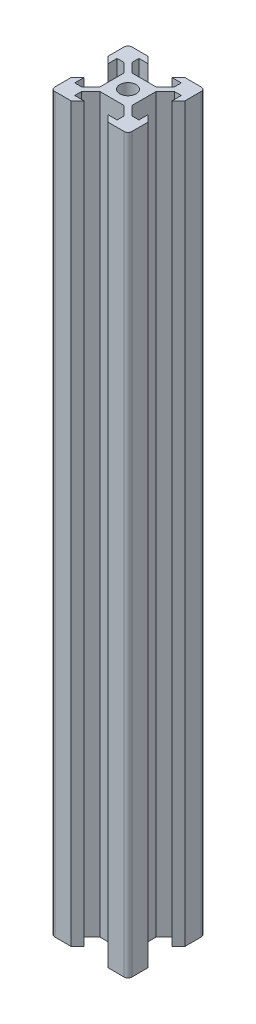
SolidWorks part; units mm, degrees
material "1060 Alloy"
ref_plane "Front Plane" through (0, 0, 0) normal (0, 0, 1) x (1, 0, 0)
ref_plane "Top Plane" through (0, 0, 0) normal (0, 1, 0) x (1, 0, 0)
ref_plane "Right Plane" through (0, 0, 0) normal (1, 0, 0) x (0, 0, -1)
ref_plane "End Plane" through (0, 190, 0) normal (0, 1, 0) x (1, 0, 0)
sketch "MasterLayoutSketch" plane through (0, 0, 0) normal (0, 1, 0) x (1, 0, 0)
  line L0 (-8.325, 3.1) -> (-8.325, 5.5)
  line L1 (-10, -10) -> (10, -10) construction
  line L2 (-10, -10) -> (-10, 10) construction
  line L3 (-10, 10) -> (10, 10) construction
  line L4 (10, -10) -> (10, 10) construction
  line L5 (-10, -10) -> (10, 10) construction
  line L6 (-10, 10) -> (10, -10) construction
  line L7 (-4.775, 10) -> (-3.1, 8.325)
  line L10 (-8.325, 5.5) -> (-6.5607, 5.5)
  line L11 (-10, 4.775) -> (-8.325, 3.1)
  line L12 (-5.5, 8.325) -> (-5.5, 6.5607)
  line L13 (-3.1, 8.325) -> (-5.5, 8.325)
  line L14 (-10, 10) -> (-10, 4.775)
  line L19 (3.1, 8.325) -> (5.5, 8.325)
  line L20 (10, 4.775) -> (8.325, 3.1)
  line L21 (-10, 10) -> (-4.775, 10)
  line L22 (-6.5607, 5.5) -> (-4.1607, 3.1)
  line L23 (-5.5, 6.5607) -> (-3.1, 4.1607)
  line L24 (5.5, 8.325) -> (5.5, 6.5607)
  line L25 (4.775, 10) -> (3.1, 8.325)
  line L26 (8.325, 5.5) -> (6.5607, 5.5)
  line L27 (8.325, 3.1) -> (8.325, 5.5)
  line L28 (10, 10) -> (4.775, 10)
  line L29 (10, 10) -> (10, 4.775)
  line L30 (5.5, 6.5607) -> (3.1, 4.1607)
  line L31 (6.5607, 5.5) -> (4.1607, 3.1)
  line L32 (8.325, -3.1) -> (8.325, -5.5)
  line L33 (4.775, -10) -> (3.1, -8.325)
  line L34 (8.325, -5.5) -> (6.5607, -5.5)
  line L35 (10, -4.775) -> (8.325, -3.1)
  line L36 (5.5, -8.325) -> (5.5, -6.5607)
  line L37 (3.1, -8.325) -> (5.5, -8.325)
  line L38 (10, -10) -> (10, -4.775)
  line L39 (10, -10) -> (4.775, -10)
  line L40 (6.5607, -5.5) -> (4.1607, -3.1)
  line L41 (5.5, -6.5607) -> (3.1, -4.1607)
  line L42 (-3.1, -8.325) -> (-5.5, -8.325)
  line L43 (-10, -4.775) -> (-8.325, -3.1)
  line L44 (-5.5, -8.325) -> (-5.5, -6.5607)
  line L45 (-4.775, -10) -> (-3.1, -8.325)
  line L46 (-8.325, -5.5) -> (-6.5607, -5.5)
  line L47 (-8.325, -3.1) -> (-8.325, -5.5)
  line L48 (-10, -10) -> (-4.775, -10)
  line L49 (-10, -10) -> (-10, -4.775)
  line L50 (-5.5, -6.5607) -> (-3.1, -4.1607)
  line L51 (-6.5607, -5.5) -> (-4.1607, -3.1)
  line L52 (-4.1607, 3.1) -> (-4.1607, -3.1)
  line L53 (-3.1, -4.1607) -> (3.1, -4.1607)
  line L54 (4.1607, -3.1) -> (4.1607, 3.1)
  line L55 (-3.1, 4.1607) -> (3.1, 4.1607)
  circle A0 centre (0, 0) radius 2.1
  point P0 (0, 0)
  point P9 (0, 0)
  dimension "D6" = 4.2
  dimension "D1" = 20
  dimension "D2" = 4
  dimension "D3" = 11
  dimension "D4" = 9.55
  dimension "D5" = 6.2
  dimension "D7" = 1.5
extrude "Main Extrusion" add sketch "MasterLayoutSketch" along normal up to surface (190 mm away) up to plane "End Plane"
fillet "Edge Fillets" radius 1 4 edges at (10, 95, -10) (10, 95, 10) (-10, 95, 10) (-10, 95, -10)
